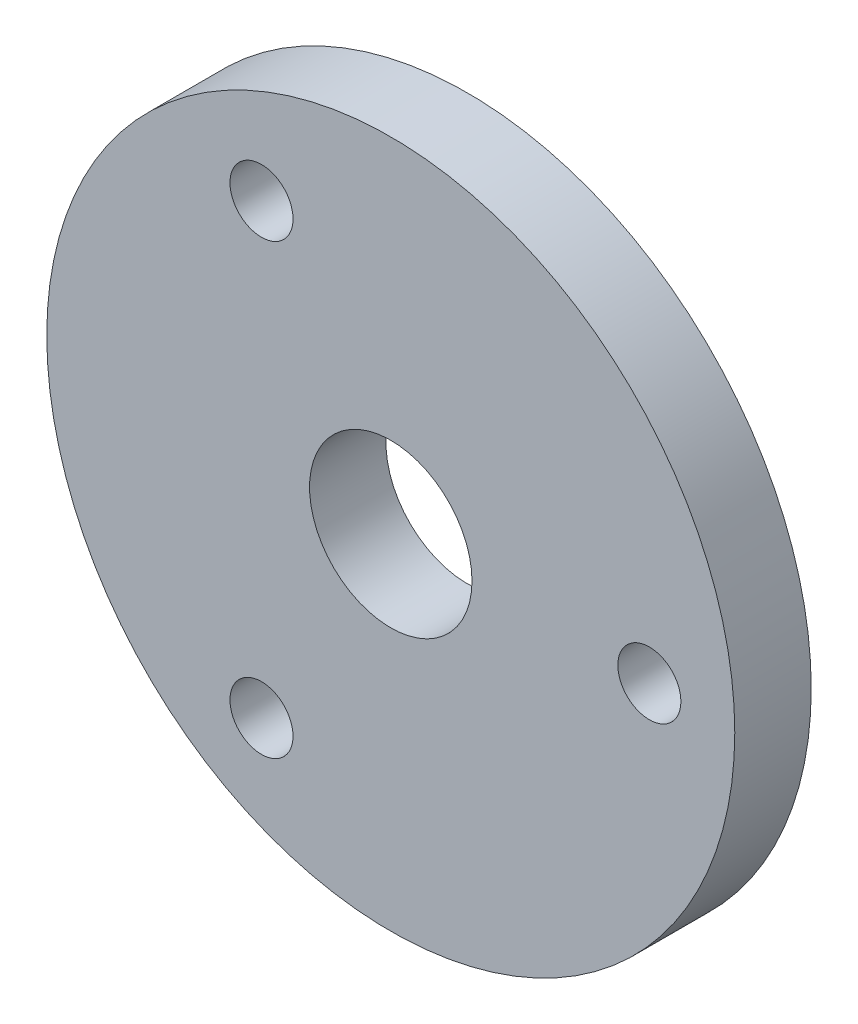
SolidWorks part; units mm, degrees
ref_plane "前视基准面" through (0, 0, 0) normal (0, 0, 1) x (1, 0, 0)
ref_plane "上视基准面" through (0, 0, 0) normal (0, 1, 0) x (1, 0, 0)
ref_plane "右视基准面" through (0, 0, 0) normal (1, 0, 0) x (0, 0, -1)
sketch "草图1" plane through (0, 0, 0) normal (0, 0, 1) x (1, 0, 0)
  circle A0 centre (-0.7367, 0.0914) radius 4.25
  circle A1 centre (-0.7367, 0.0914) radius 13.53 construction
  circle A2 centre (12.7933, 0.0914) radius 1.65
  circle A5 centre (-0.7367, 0.0914) radius 18
  circle A6 centre (-7.5017, -11.6259) radius 1.65
  circle A7 centre (-7.5017, 11.8087) radius 1.65
  dimension "D2" = 3
extrude "凸台-拉伸1" add sketch "草图1" along normal blind 4 contours A5
